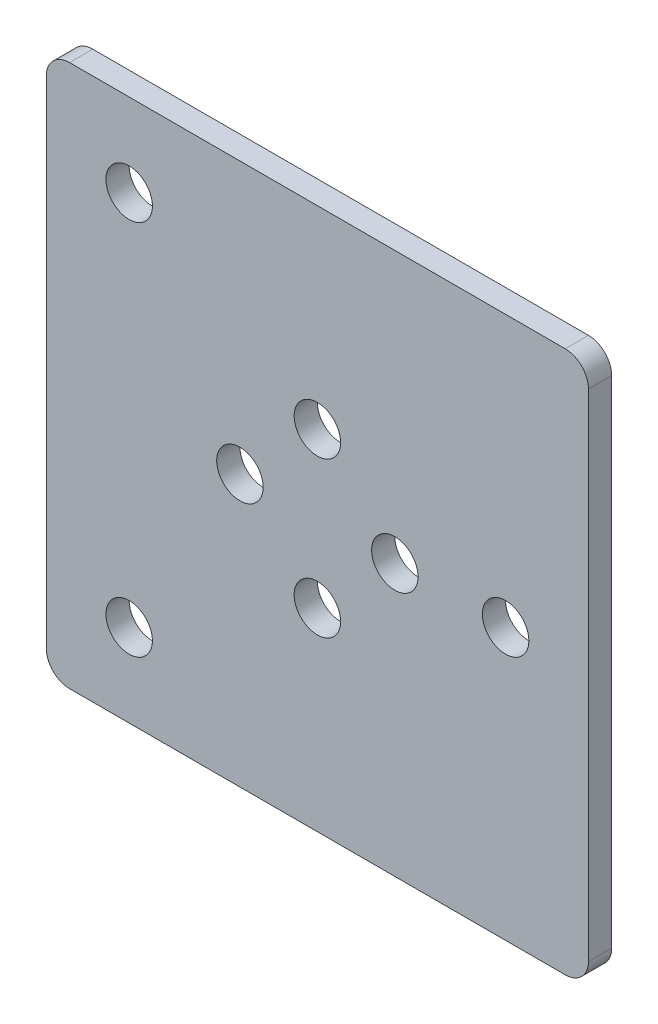
SolidWorks part; units mm, degrees
material "Plain Carbon Steel"
ref_plane "Front" through (0, 0, 0) normal (0, 0, 1) x (1, 0, 0)
ref_plane "Top" through (0, 0, 0) normal (0, 1, 0) x (1, 0, 0)
ref_plane "Right" through (0, 0, 0) normal (1, 0, 0) x (0, 0, -1)
sketch "Sketch3" plane through (0, 0, 0) normal (0, 0, 1) x (1, 0, 0)
  line L1 (-35, 35) -> (35, 35)
  line L2 (-35, 35) -> (-35, -35)
  line L3 (-35, -35) -> (35, -35)
  line L4 (35, 35) -> (35, -35)
  line L5 (-35, 35) -> (35, -35) construction
  line L6 (-35, -35) -> (35, 35) construction
  circle A0 centre (0, 10) radius 3
  circle A1 centre (-24.3, 24.3) radius 3
  circle A2 centre (10, 0) radius 3
  circle A3 centre (0, -10) radius 3
  circle A4 centre (-10, 0) radius 3
  circle A5 centre (10, 0) radius 3
  circle A7 centre (0, -10) radius 3
  circle A9 centre (-10, 0) radius 3
  circle A10 centre (-24.3, -24.3) radius 3
  circle A13 centre (24.3, 24.3) radius 3 [skipped]
  circle A14 centre (24.3, -24.3) radius 3 [skipped]
  circle A15 centre (24.3, 0) radius 3
  point P0 (0, 0)
  point P10 (0, 0)
  point P15 (0, 0)
  point P18 (0, 0)
  point P21 (0, 0)
  point P23 (0, 0)
  point P28 (0, 0)
  point P33 (0, 0)
  point P38 (0, 0)
  dimension "D3" = 6
  dimension "D4" = 6
  dimension "D9" = 6
  dimension "D10" = 10.7
  dimension "D1" = 70
  dimension "D2" = 70
  dimension "D5" = 10.7
  dimension "D6" = 10
  dimension "D7" = 4
  dimension "D8" = 4
extrude "Boss-Extrude2" add sketch "Sketch3" along normal blind 3
fillet "Fillet2" radius 3 4 edges at (-35, -35, 1.5) (35, -35, 1.5) (35, 35, 1.5) (-35, 35, 1.5)
